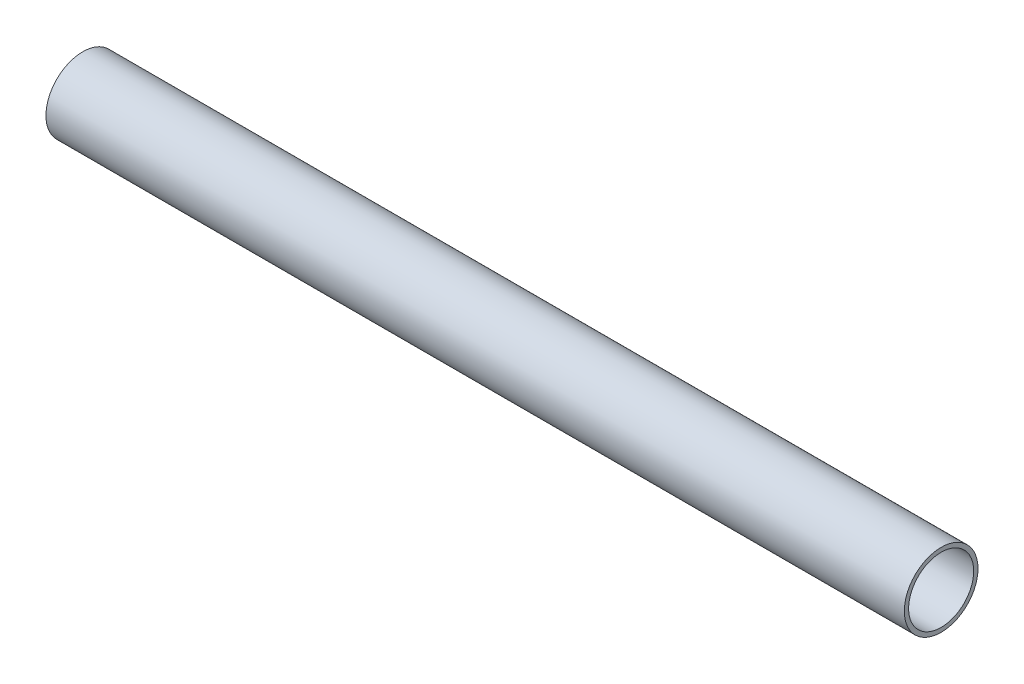
SolidWorks part; units mm, degrees
material "PVC Rígido"
ref_plane "Alzado" through (0, 0, 0) normal (0, 0, 1) x (1, 0, 0)
ref_plane "Planta" through (0, 0, 0) normal (0, 1, 0) x (1, 0, 0)
ref_plane "Vista lateral" through (0, 0, 0) normal (1, 0, 0) x (0, 0, -1)
sketch "Croquis2" plane through (0, 0, 0) normal (1, 0, 0) x (0, 0, -1)
  circle A0 centre (0, 0) radius 75.85
  circle A1 centre (0, 0) radius 85.85
  dimension "D1" = 151.7
  dimension "D2" = 10
extrude "Saliente-Extruir1" add sketch "Croquis2" along normal blind 2000
